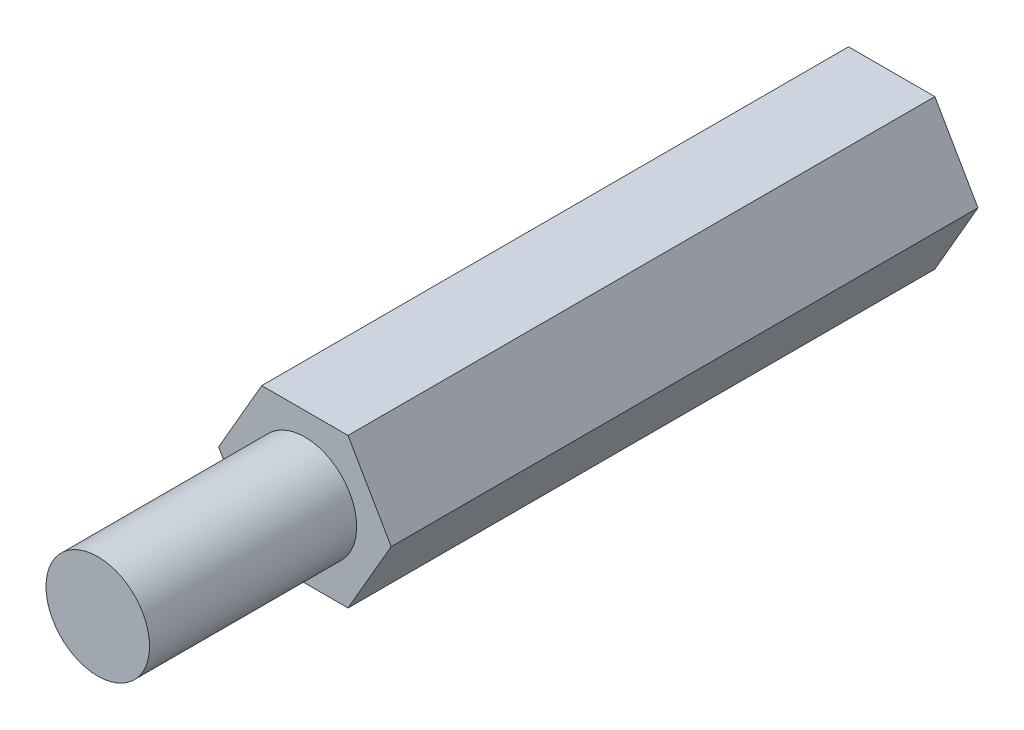
SolidWorks part; units mm, degrees
material "普通碳钢"
ref_plane "前视" through (0, 0, 0) normal (0, 0, 1) x (1, 0, 0)
ref_plane "上视" through (0, 0, 0) normal (0, 1, 0) x (1, 0, 0)
ref_plane "右视" through (0, 0, 0) normal (1, 0, 0) x (0, 0, -1)
sketch "草图1" plane through (0, 0, 0) normal (0, 0, 1) x (1, 0, 0)
  line L0 (0, 0) -> (2.5, 0)
  line L1 (2.5, 0) -> (3.75, -2.1651)
  line L2 (3.75, -2.1651) -> (2.5, -4.3301)
  line L3 (2.5, -4.3301) -> (0, -4.3301)
  line L4 (0, -4.3301) -> (-1.25, -2.1651)
  line L5 (-1.25, -2.1651) -> (0, 0)
  dimension "D1" = 5
  dimension "D2" = 5
extrude "凸台-拉伸1" add sketch "草图1" along normal blind 17
hole_wizard "M3 螺纹孔1" positions "草图3" profile "草图2" tap size "M3" standard "GB" end condition through all
sketch "草图3" plane through (0, 0, 17) normal (0, 0, 1) x (1, 0, 0)
  line L0 (-1.25, -2.1651) -> (3.75, -2.1651) construction
  line L2 (1.25, 0) -> (1.25, -4.3301) construction
  line L3 (2.5, 0) -> (0, 0) construction
  line L4 (0, -4.3301) -> (2.5, -4.3301) construction
  point P0 (1.25, -2.1651)
cosmetic thread "孔螺蚊线1" parameters "D2"=3
sketch "草图2" plane through (1.25, -2.1651, 17) normal (1, 0, 0) x (0, -1, 0)
  line L0 (0, 0) -> (0, 17)
  line L1 (0, 17) -> (1.25, 17)
  line L2 (1.25, 17) -> (1.25, 0)
  line L5 (1.25, 0) -> (0, 0)
  line L11 (0, -6.35) -> (0, 107.95) construction
  dimension "通孔螺纹孔钻头直径" = 2.5
  dimension "通孔螺纹孔钻头深度" = 17
sketch "草图4" plane through (0, 0, 17) normal (0, 0, 1) x (1, 0, 0)
  circle A0 centre (1.25, -2.1651) radius 1.5
  dimension "D1" = 3
extrude "凸台-拉伸2" add sketch "草图4" along normal blind 6
cosmetic thread "装饰螺纹线1" parameters "D2"=2.459
